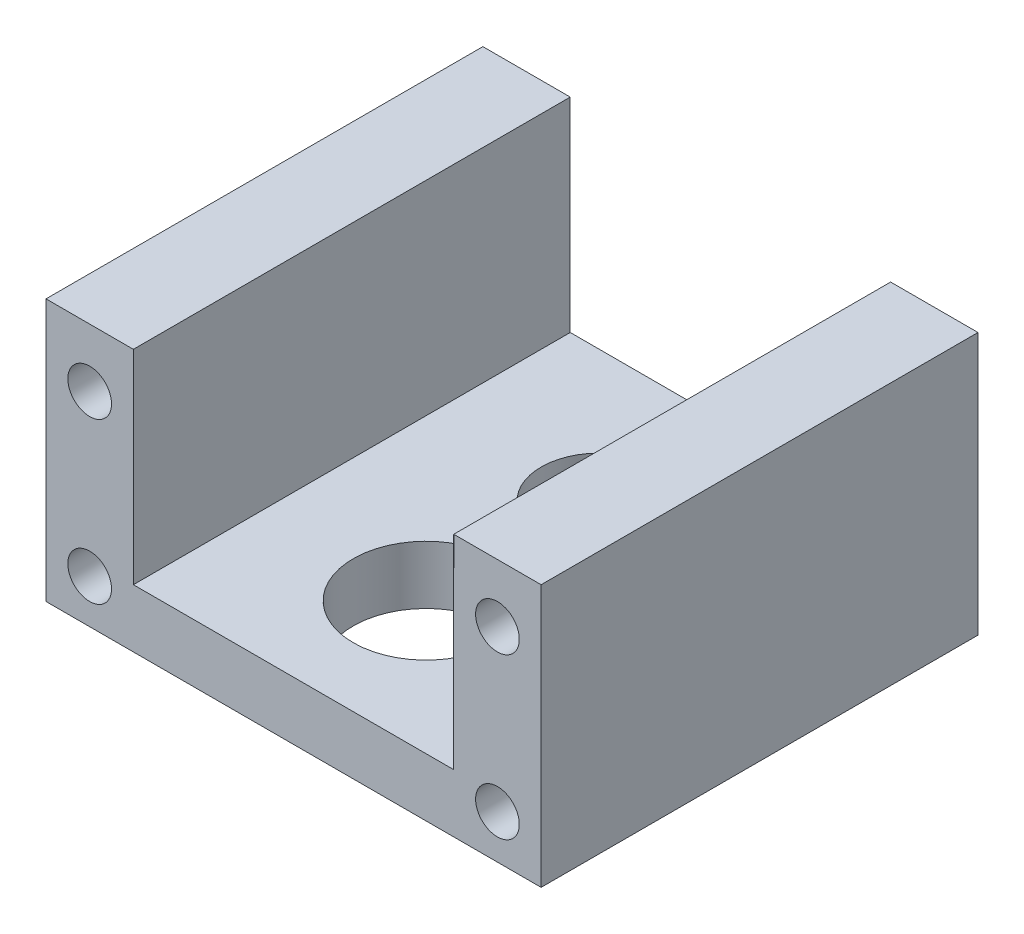
SolidWorks part; units mm, degrees
material "PLA"
ref_plane "前视基准面" through (0, 0, 0) normal (0, 0, 1) x (1, 0, 0)
ref_plane "上视基准面" through (0, 0, 0) normal (0, 1, 0) x (1, 0, 0)
ref_plane "右视基准面" through (0, 0, 0) normal (1, 0, 0) x (0, 0, -1)
sketch "草图1" plane through (0, 0, 0) normal (0, 1, 0) x (1, 0, 0)
  line L1 (17, -15) -> (-17, -15)
  line L2 (17, -15) -> (17, 15)
  line L3 (17, 15) -> (-17, 15)
  line L4 (-17, -15) -> (-17, 15)
  line L5 (17, -15) -> (-17, 15) construction
  line L6 (17, 15) -> (-17, -15) construction
  circle A0 centre (0, -5.9) radius 5
  circle A2 centre (0, 6) radius 4
  point P0 (0, 0)
  dimension "D3" = 10
  dimension "D4" = 9.1
  dimension "D5" = 8
  dimension "D1" = 30
  dimension "D2" = 34
  dimension "D6" = 11.9
extrude "凸台-拉伸1" add sketch "草图1" along normal blind 4 contours A2 L3 L4 L1 L2 A0
sketch "草图3" plane through (0, 4, 0) normal (0, 1, 0) x (1, 0, 0)
  line L1 (-17, 15) -> (-11, 15)
  line L2 (-17, 15) -> (-17, -15)
  line L3 (-17, -15) -> (-11, -15)
  line L4 (-11, 15) -> (-11, -15)
  line L5 (17, -15) -> (-17, -15) construction
  line L7 (17, 15) -> (11, 15)
  line L8 (17, 15) -> (17, -15)
  line L9 (17, -15) -> (11, -15)
  line L10 (11, 15) -> (11, -15)
  dimension "D1" = 30
  dimension "D2" = 6
  dimension "D3" = 30
  dimension "D4" = 6
extrude "凸台-拉伸2" add sketch "草图3" along normal blind 15
sketch "草图4" plane through (0, 0, -15) normal (0, 0, -1) x (-1, 0, 0)
  line L0 (-17, 19) -> (-11, 19) construction
  line L1 (0, 23.2592) -> (0, -11.1091) construction
  circle A0 centre (-14, 3) radius 1.5
  circle A1 centre (-14, 14) radius 1.5
  circle A2 centre (14, 3) radius 1.5
  circle A3 centre (14, 14) radius 1.5
  point P7 (-14, 19)
  dimension "D1" = 3
  dimension "D2" = 3
  dimension "D3" = 5
  dimension "D4" = 11
extrude "切除-拉伸1" cut sketch "草图4" against normal through all
sketch "草图5" plane through (0, 0, -15) normal (0, 0, -1) x (-1, 0, 0)
  line L0 (-17, 19) -> (-17, 0) construction
  line L1 (17, 19) -> (-17, 19)
  line L2 (17, 19) -> (17, 18)
  line L3 (17, 18) -> (-17, 18)
  line L4 (-17, 19) -> (-17, 18)
  dimension "D1" = 1
extrude "切除-拉伸2" cut sketch "草图5" against normal through all
chamfer "倒角1" distance 1 1 edges at (0, 0, -2)
